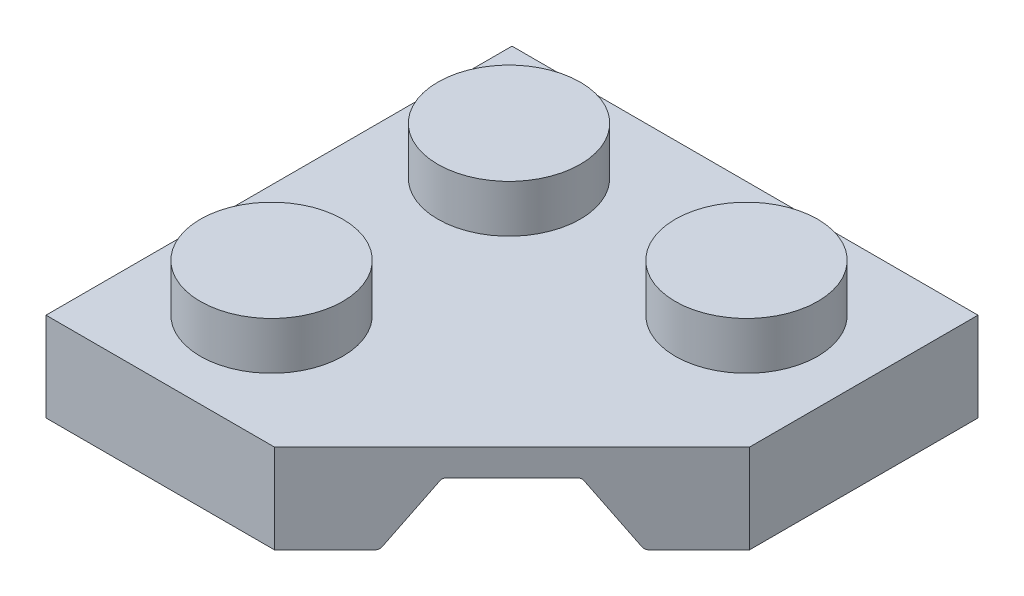
SolidWorks part; units mm, degrees
material "ABS"
ref_plane "Front Plane" through (0, 0, 0) normal (0, 0, 1) x (1, 0, 0)
ref_plane "Top Plane" through (0, 0, 0) normal (0, 1, 0) x (1, 0, 0)
ref_plane "Right Plane" through (0, 0, 0) normal (1, 0, 0) x (0, 0, -1)
sketch "Sketch1" plane through (0, 0, 0) normal (0, 1, 0) x (1, 0, 0)
  line L1 (-7.85, -7.85) -> (7.85, -7.85)
  line L2 (-7.85, -7.85) -> (-7.85, 7.85)
  line L3 (-7.85, 7.85) -> (7.85, 7.85)
  line L4 (7.85, -7.85) -> (7.85, 7.85)
  line L5 (-7.85, -7.85) -> (7.85, 7.85) construction
  line L6 (-7.85, 7.85) -> (7.85, -7.85) construction
  point P0 (0, 0)
  dimension "D1" = 15.7
extrude "Boss-Extrude1" add sketch "Sketch1" along normal mid plane 3
sketch "Sketch3" plane through (0, 1.5, 0) normal (0, 1, 0) x (1, 0, 0)
  line L0 (7.85, -7.85) -> (7.85, 7.85) construction
  line L1 (7.85, 7.85) -> (-7.85, 7.85) construction
  circle A1 centre (3.95, 3.95) radius 2.4
  dimension "D1" = 3.9
  dimension "D3" = 4.8
  dimension "D2" = 3.9
extrude "Boss-Extrude2" add sketch "Sketch3" along normal blind 1.6
sketch "Sketch4" plane through (0, -1.5, 0) normal (0, -1, 0) x (1, 0, 0)
  line L0 (-7.15, 7.15) -> (-1.15, 7.15)
  line L1 (-1.15, 7.15) -> (7.15, -1.15)
  line L2 (7.15, -1.15) -> (7.15, -7.15)
  line L3 (7.15, -7.15) -> (-7.15, -7.15)
  line L4 (-7.15, -7.15) -> (-7.15, 7.15)
  line L5 (-7.85, 7.85) -> (7.85, 7.85) construction
  line L6 (-7.85, -7.85) -> (-7.85, 7.85) construction
  line L7 (7.85, -7.85) -> (-7.85, -7.85) construction
  line L8 (7.85, 7.85) -> (7.85, -7.85) construction
  dimension "D1" = 0.7
  dimension "D2" = 0.7
  dimension "D3" = 0.7
  dimension "D4" = 0.7
  dimension "D5" = 6
  dimension "D6" = 6
extrude "Cut-Extrude1" cut sketch "Sketch4" against normal offset from surface (2.1 mm away) 0.9 up to face at (3.95, 1.5, -6.35)
sketch "Sketch6" plane through (0, -1.5, 0) normal (0, -1, 0) x (1, 0, 0)
  line L0 (-0.1529, 7.85) -> (7.85, -0.1529)
  line L1 (-7.85, 7.85) -> (7.85, 7.85) construction
  line L5 (7.85, 7.85) -> (-0.1529, 7.85)
  line L6 (7.15, -1.15) -> (-1.15, 7.15) construction
  line L7 (7.85, 7.85) -> (7.85, -7.85) construction
  line L8 (7.85, 7.85) -> (7.85, -0.1529)
  dimension "D1" = 1.2
extrude "Cut-Extrude2" cut sketch "Sketch6" against normal through all
pattern_linear "LPattern2" count 2 spacing 8 along (-1, 0, 0) count 2 spacing 8 along (0, 0, 1) skipping (0, 1) of "Boss-Extrude2"
sketch "Sketch7" plane through (0, 0.6, 0) normal (0, -1, 0) x (1, 0, 0)
  circle A0 centre (0, 0) radius 1.5
  circle A1 centre (0, 0) radius 1
  dimension "D1" = 3
  dimension "D2" = 2
extrude "Boss-Extrude3" add sketch "Sketch7" along normal offset from surface (1.9 mm away) 0.2 up to face at (-0.0306, -1.5, -0.0306)
sketch "Sketch10" plane through (0, 0.6, 0) normal (0, -1, 0) x (1, 0, 0)
  line L0 (-7.85, -7.85) -> (-7.85, 7.85) construction
  line L1 (-7.85, 7.85) -> (-0.1529, 7.85) construction
  circle A0 centre (-3.95, 3.95) radius 1.3
  dimension "D1" = 2.6
  dimension "D2" = 3.9
  dimension "D3" = 3.9
extrude "Cut-Extrude3" cut sketch "Sketch10" against normal blind 1.7
pattern_linear "LPattern3" count 2 spacing 8 along (0, 0, -1) count 2 spacing 8 along (1, 0, 0) skipping (0, 1) of "Cut-Extrude3"
sketch "Sketch11" plane through (3.8485, 0, 3.8485) normal (0.7071, 0, 0.7071) x (0.7071, 0, -0.7071)
  line L0 (-1.6589, 0.6) -> (1.6589, 0.6)
  line L1 (-1.6589, 0.6) -> (-3.1589, -1.5)
  line L3 (-5.6589, -1.5) -> (5.6589, -1.5) construction
  line L4 (-5.6589, 1.5) -> (5.6589, 1.5) construction
  line L7 (1.6589, 0.6) -> (3.1589, -1.5)
  line L8 (5.6589, 1.5) -> (5.6589, -1.5) construction
  dimension "D1" = 0.9
  dimension "D2" = 4
  dimension "D3" = 4
  dimension "D4" = 2.5
  dimension "D5" = 2.5
extrude "Cut-Extrude4" cut sketch "Sketch11" against normal blind 1.7 and the other way through all flip side to cut
fillet "Fillet1" radius 0.2 4 edges at (1.1906, -1.5, 5.658) (5.658, -1.5, 1.1906) (4.5973, 0.6, 2.2512) (2.2512, 0.6, 4.5973)
